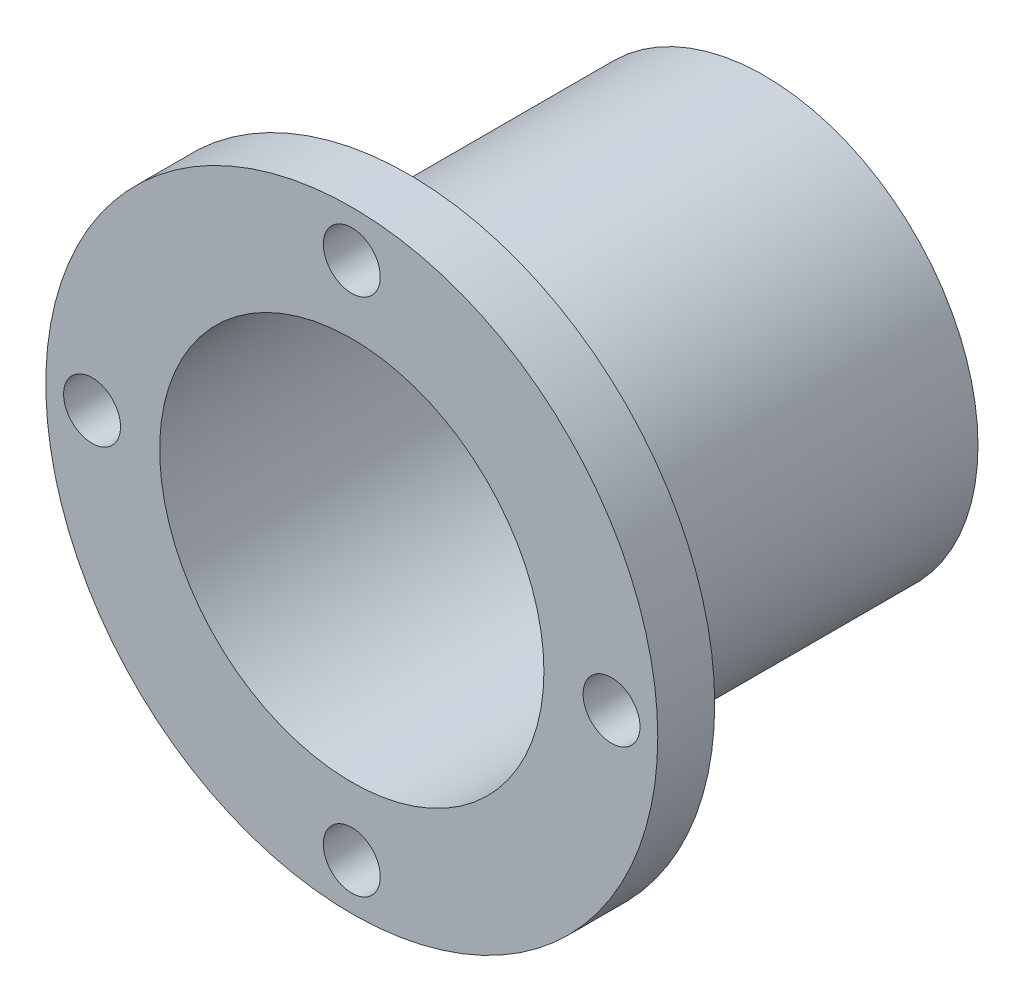
SolidWorks part; units mm, degrees
ref_plane "前视基准面" through (0, 0, 0) normal (0, 0, 1) x (1, 0, 0)
ref_plane "上视基准面" through (0, 0, 0) normal (0, 1, 0) x (1, 0, 0)
ref_plane "右视基准面" through (0, 0, 0) normal (1, 0, 0) x (0, 0, -1)
sketch "草图1" plane through (0, 0, 0) normal (0, 0, 1) x (1, 0, 0)
  circle A0 centre (0, 0) radius 13.5
  circle A1 centre (0, 0) radius 15
  dimension "D1" = 27
  dimension "D2" = 30
extrude "凸台-拉伸1" add sketch "草图1" along normal blind 25
sketch "草图2" plane through (0, 0, 25) normal (0, 0, 1) x (1, 0, 0)
  circle A0 centre (0, 0) radius 21.5
  circle A1 centre (0, 0) radius 13.5
  circle A4 centre (0, 0) radius 18.25 construction
  circle A5 centre (0, 18.25) radius 2
  circle A6 centre (18.25, 0) radius 2
  circle A7 centre (0, -18.25) radius 2
  circle A8 centre (-18.25, 0) radius 2
  dimension "D1" = 43
  dimension "D2" = 27
  dimension "D3" = 4
  dimension "D4" = 36.5
  dimension "D5" = 4
extrude "凸台-拉伸3" add sketch "草图2" along normal blind 4
fillet "圆角2" radius 1 1 edges at (15, 0, 25)
